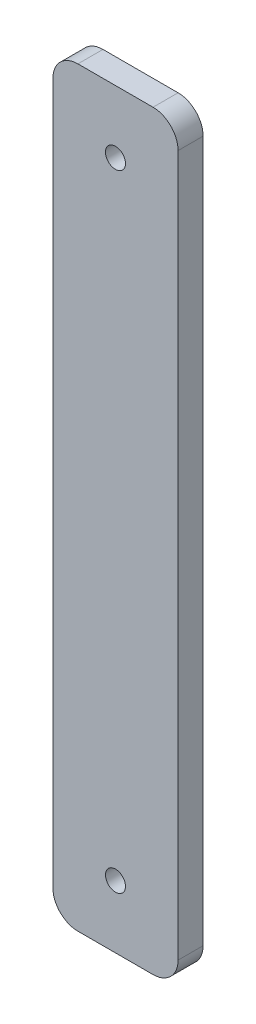
SolidWorks part; units mm, degrees
ref_plane "Front Plane" through (0, 0, 0) normal (0, 0, 1) x (1, 0, 0)
ref_plane "Top Plane" through (0, 0, 0) normal (0, 1, 0) x (1, 0, 0)
ref_plane "Right Plane" through (0, 0, 0) normal (1, 0, 0) x (0, 0, -1)
sketch "Sketch1" plane through (0, 0, 0) normal (0, 0, 1) x (1, 0, 0)
  line L0 (0, -150) -> (50, -150) construction
  line L1 (0, 0) -> (50, 0)
  line L2 (0, 0) -> (0, -300)
  line L3 (0, -300) -> (50, -300)
  line L4 (50, 0) -> (50, -300)
  circle A0 centre (25, -275) radius 4
  circle A1 centre (25, -25) radius 4
  dimension "D3" = 25
  dimension "D1" = 50
  dimension "D2" = 300
  dimension "D4" = 25
extrude "Boss-Extrude1" add sketch "Sketch1" along normal blind 10
fillet "Fillet1" radius 10 4 edges at (50, -300, 5) (0, -300, 5) (0, 0, 5) (50, 0, 5)
